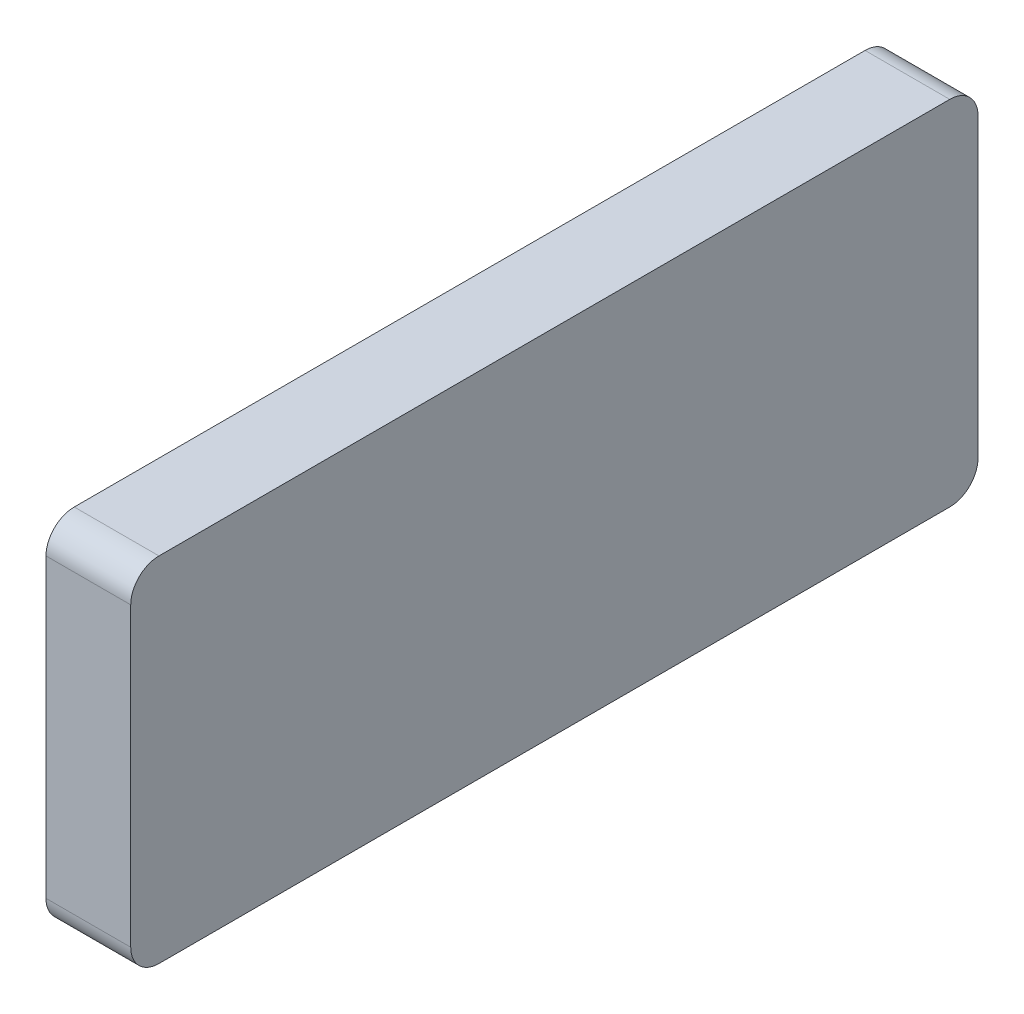
SolidWorks part; units mm, degrees
ref_plane "Ön Düzlem" through (0, 0, 0) normal (0, 0, 1) x (1, 0, 0)
ref_plane "Üst Düzlem" through (0, 0, 0) normal (0, 1, 0) x (1, 0, 0)
ref_plane "Sağ Düzlem" through (0, 0, 0) normal (1, 0, 0) x (0, 0, -1)
sketch "Sketch1" plane through (0, 0, 0) normal (1, 0, 0) x (0, 0, -1)
  line L0 (0, 0) -> (60, 0)
  line L1 (60, 0) -> (60, 25)
  line L2 (60, 25) -> (0, 25)
  line L3 (0, 25) -> (0, 0)
  dimension "D1" = 60
  dimension "D2" = 25
extrude "Boss-Extrude1" add sketch "Sketch1" along normal blind 6
fillet "Fillet1" radius 2 4 edges at (3, 0, 0) (3, 0, -60) (3, 25, -60) (3, 25, 0)
ref_plane "Plane1" through (0, 0, -30) normal (0, 0, 1) x (1, 0, 0)
sketch "Sketch3" plane through (0, 0, 0) normal (-1, 0, 0) x (0, 0, 1)
  line L4 (-58, 0) -> (-2, 0)
  line L5 (0, 2) -> (0, 23)
  line L6 (-2, 25) -> (-58, 25)
  line L7 (-60, 23) -> (-60, 2)
  line L8 (-58, 0) -> (-2, 0)
  line L9 (0, 2) -> (0, 23)
  line L10 (-2, 25) -> (-58, 25)
  line L11 (-60, 23) -> (-60, 2)
  arc A4 (-2, 0) -> (0, 2) centre (-2, 2) ccw
  arc A5 (0, 23) -> (-2, 25) centre (-2, 23) ccw
  arc A6 (-58, 25) -> (-60, 23) centre (-58, 23) ccw
  arc A7 (-60, 2) -> (-58, 0) centre (-58, 2) ccw
  arc A8 (-2, 0) -> (0, 2) centre (-2, 2) ccw
  arc A9 (0, 23) -> (-2, 25) centre (-2, 23) ccw
  arc A10 (-58, 25) -> (-60, 23) centre (-58, 23) ccw
  arc A11 (-60, 2) -> (-58, 0) centre (-58, 2) ccw
  dimension "D1" = 0
ref_plane "Plane2" through (0, 12.5, 0) normal (0, 1, 0) x (1, 0, 0)
